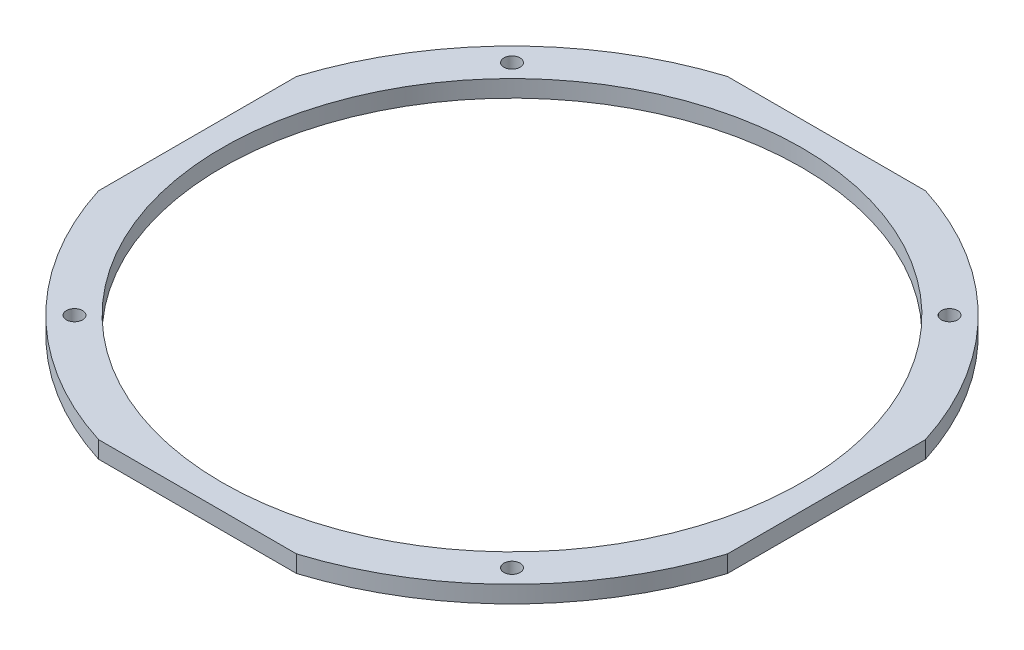
SolidWorks part; units mm, degrees
material "ABS"
ref_plane "前视基准面" through (0, 0, 0) normal (0, 0, 1) x (1, 0, 0)
ref_plane "上视基准面" through (0, 0, 0) normal (0, 1, 0) x (1, 0, 0)
ref_plane "右视基准面" through (0, 0, 0) normal (1, 0, 0) x (0, 0, -1)
sketch "草图1" plane through (0, 0, 0) normal (0, 1, 0) x (1, 0, 0)
  circle A0 centre (0, 0) radius 57.15
  circle A1 centre (0, 0) radius 65
  dimension "D1" = 114.3
  dimension "D2" = 130
extrude "凸台-拉伸1" add sketch "草图1" along normal blind 3.35
sketch "草图2" plane through (0, 3.35, 0) normal (0, 1, 0) x (1, 0, 0)
  line L0 (-93.8116, 0) -> (93.8459, 0) construction
  line L1 (0, 78.4608) -> (0, -80.5169) construction
  line L3 (-62, 62) -> (62, 62)
  line L4 (-62, 62) -> (-62, -62)
  line L5 (-62, -62) -> (62, -62)
  line L6 (62, 62) -> (62, -62)
  line L7 (0, -62) -> (0, 62) construction
  line L8 (-62, 0) -> (62, 0) construction
  line L9 (-81.1075, 76.4199) -> (81.1417, 76.4199)
  line L10 (-81.1075, 76.4199) -> (-81.1075, -76.4199)
  line L11 (-81.1075, -76.4199) -> (81.1417, -76.4199)
  line L12 (81.1417, 76.4199) -> (81.1417, -76.4199)
  line L13 (0.0171, -76.4199) -> (0.0171, 76.4199) construction
  line L14 (-81.1075, 0) -> (81.1417, 0) construction
  point P5 (0.0171, 0)
  point P8 (0, 0)
  dimension "D1" = 124
  dimension "D2" = 124
extrude "切除-拉伸1" cut sketch "草图2" against normal blind 3.35
sketch "草图3" plane through (0, 3.35, 0) normal (0, 1, 0) x (1, 0, 0)
  line L0 (-73.4142, 0) -> (83.0394, 0) construction
  line L1 (0, 95.621) -> (0, -76.7508) construction
  line L2 (0, 0) -> (54.4444, -54.4444) construction
  circle A0 centre (0, 0) radius 61 construction
  circle A1 centre (43.1335, -43.1335) radius 1.6
  circle A2 centre (-43.1335, -43.1335) radius 1.6
  circle A3 centre (-43.1335, 43.1335) radius 1.6
  circle A4 centre (43.1335, 43.1335) radius 1.6
  point P7 (43.1335, -43.1335)
  dimension "D1" = 122
  dimension "D3" = 3.2
  dimension "D2" = 4
extrude "切除-拉伸2" cut sketch "草图3" against normal blind 3.35
